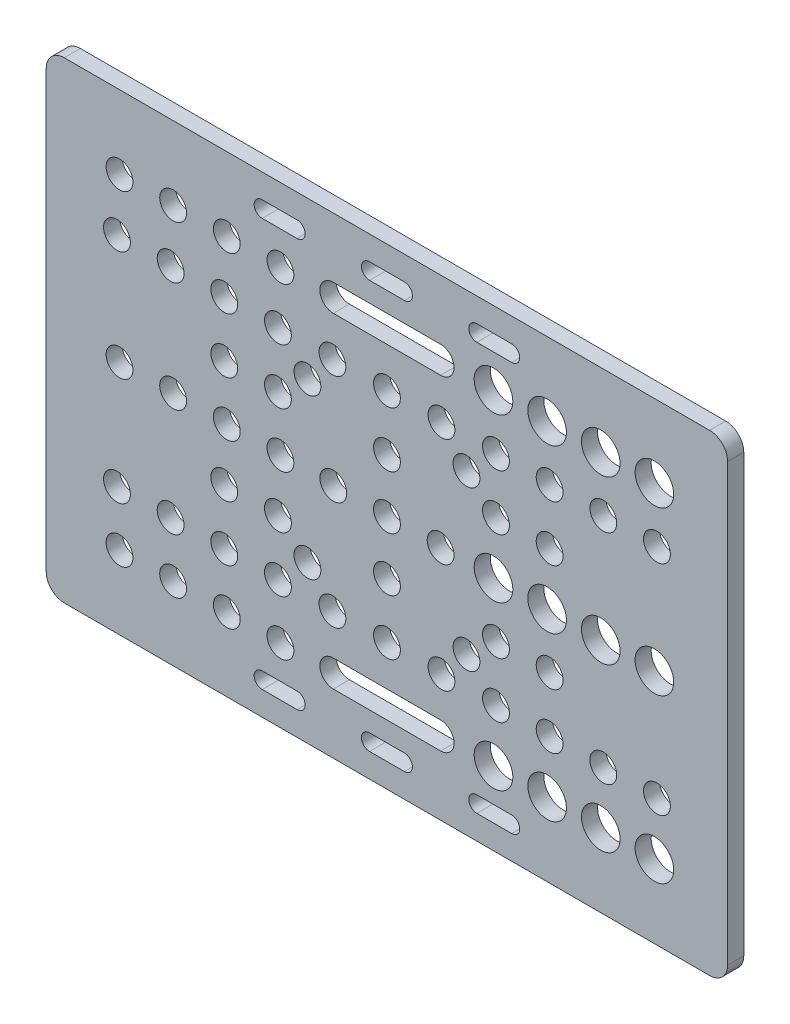
SolidWorks part; units mm, degrees
material "6063-T6"
ref_plane "Front" through (0, 0, 0) normal (0, 0, 1) x (1, 0, 0)
ref_plane "Top" through (0, 0, 0) normal (0, 1, 0) x (1, 0, 0)
ref_plane "Right" through (0, 0, 0) normal (1, 0, 0) x (0, 0, -1)
sketch "Sketch1" plane through (0, 0, 0) normal (0, 0, 1) x (1, 0, 0)
  line L0 (-60.14, 44) -> (-63.5, 40.64) construction
  line L1 (-60.14, -44) -> (60.14, -44)
  line L2 (-63.5, -40.64) -> (-63.5, 40.64)
  line L3 (-60.14, 44) -> (60.14, 44)
  line L4 (63.5, -40.64) -> (63.5, 40.64)
  line L5 (-62.924, -42.5213) -> (62.924, 42.5213) construction
  line L6 (-62.924, 42.5213) -> (62.924, -42.5213) construction
  line L7 (60.14, 44) -> (63.5, 40.64) construction
  line L8 (63.5, -40.64) -> (60.14, -44) construction
  line L9 (-63.5, -40.64) -> (-60.14, -44) construction
  line L10 (-63.5, 0) -> (63.5, 0) construction
  line L11 (0, 44) -> (0, -44) construction
  line L12 (-63.5, -30.32) -> (63.5, -30.32) construction
  line L13 (-10, -30.32) -> (10, -30.32) construction
  line L14 (-10, -27.82) -> (10, -27.82)
  line L15 (-10, -32.82) -> (10, -32.82)
  line L16 (-10, 30.32) -> (10, 30.32) construction
  line L17 (-10, 27.82) -> (10, 27.82)
  line L18 (-10, 32.82) -> (10, 32.82)
  line L19 (-63.5, -38.02) -> (63.5, -38.02) construction
  line L20 (-3.25, -38.02) -> (3.25, -38.02) construction
  line L21 (-3.25, -36.52) -> (3.25, -36.52)
  line L22 (-3.25, -39.52) -> (3.25, -39.52)
  line L23 (-23.25, -38.02) -> (-16.75, -38.02) construction
  line L24 (-23.25, -36.52) -> (-16.75, -36.52)
  line L25 (-23.25, -39.52) -> (-16.75, -39.52)
  line L26 (23.25, -38.02) -> (16.75, -38.02) construction
  line L27 (23.25, -36.52) -> (16.75, -36.52)
  line L28 (23.25, -39.52) -> (16.75, -39.52)
  line L29 (-23.25, 38.02) -> (-16.75, 38.02) construction
  line L30 (-23.25, 36.52) -> (-16.75, 36.52)
  line L31 (-23.25, 39.52) -> (-16.75, 39.52)
  line L32 (-3.25, 38.02) -> (3.25, 38.02) construction
  line L33 (-3.25, 36.52) -> (3.25, 36.52)
  line L34 (-3.25, 39.52) -> (3.25, 39.52)
  line L35 (23.25, 38.02) -> (16.75, 38.02) construction
  line L36 (23.25, 36.52) -> (16.75, 36.52)
  line L37 (23.25, 39.52) -> (16.75, 39.52)
  line L38 (-63.5, -20.32) -> (63.5, -20.32) construction
  line L39 (-63.5, -10) -> (63.5, -10) construction
  line L40 (-63.5, -14.82) -> (63.5, -14.82) construction
  arc A0 (-60.14, 44) -> (-63.5, 40.64) centre (-60.14, 40.64) ccw
  arc A1 (63.5, 40.64) -> (60.14, 44) centre (60.14, 40.64) ccw
  arc A2 (60.14, -44) -> (63.5, -40.64) centre (60.14, -40.64) ccw
  arc A3 (-63.5, -40.64) -> (-60.14, -44) centre (-60.14, -40.64) ccw
  circle A4 centre (0, 0) radius 2.5
  circle A5 centre (-49.845, 0) radius 2.5
  circle A6 centre (49.845, 0) radius 3.6
  circle A7 centre (-19.855, -30.32) radius 2.5
  circle A8 centre (19.855, -30.32) radius 3.6
  circle A9 centre (-29.85, -30.32) radius 2.5
  circle A10 centre (-39.85, -30.32) radius 2.5
  circle A11 centre (-49.845, -30.32) radius 2.5
  circle A12 centre (49.845, -30.32) radius 3.6
  circle A13 centre (39.85, -30.32) radius 3.6
  circle A14 centre (29.85, -30.32) radius 3.6
  circle A15 centre (49.845, 30.32) radius 3.6
  circle A16 centre (39.85, 30.32) radius 3.6
  circle A17 centre (29.85, 30.32) radius 3.6
  circle A18 centre (19.855, 30.32) radius 3.6
  circle A19 centre (-19.855, 30.32) radius 2.5
  circle A20 centre (-29.85, 30.32) radius 2.5
  circle A21 centre (-39.85, 30.32) radius 2.5
  circle A22 centre (-49.845, 30.32) radius 2.5
  arc A23 (-10, -27.82) -> (-10, -32.82) centre (-10, -30.32) ccw
  arc A24 (10, -32.82) -> (10, -27.82) centre (10, -30.32) ccw
  arc A25 (-10, 27.82) -> (-10, 32.82) centre (-10, 30.32) cw
  arc A26 (10, 32.82) -> (10, 27.82) centre (10, 30.32) cw
  arc A27 (-3.25, -36.52) -> (-3.25, -39.52) centre (-3.25, -38.02) ccw
  arc A28 (3.25, -39.52) -> (3.25, -36.52) centre (3.25, -38.02) ccw
  arc A29 (-23.25, -36.52) -> (-23.25, -39.52) centre (-23.25, -38.02) ccw
  arc A30 (-16.75, -39.52) -> (-16.75, -36.52) centre (-16.75, -38.02) ccw
  arc A31 (23.25, -36.52) -> (23.25, -39.52) centre (23.25, -38.02) cw
  arc A32 (16.75, -39.52) -> (16.75, -36.52) centre (16.75, -38.02) cw
  arc A33 (-23.25, 36.52) -> (-23.25, 39.52) centre (-23.25, 38.02) cw
  arc A34 (-16.75, 39.52) -> (-16.75, 36.52) centre (-16.75, 38.02) cw
  arc A35 (-3.25, 36.52) -> (-3.25, 39.52) centre (-3.25, 38.02) cw
  arc A36 (3.25, 39.52) -> (3.25, 36.52) centre (3.25, 38.02) cw
  arc A37 (23.25, 36.52) -> (23.25, 39.52) centre (23.25, 38.02) ccw
  arc A38 (16.75, 39.52) -> (16.75, 36.52) centre (16.75, 38.02) ccw
  circle A39 centre (-50.32, -20.32) radius 2.5
  circle A40 centre (-40.32, -20.32) radius 2.5
  circle A41 centre (-30.32, -20.32) radius 2.5
  circle A42 centre (-20.32, -20.32) radius 2.5
  circle A43 centre (50.32, -20.32) radius 2.5
  circle A44 centre (40.32, -20.32) radius 2.5
  circle A45 centre (30.32, -20.32) radius 2.5
  circle A46 centre (20.32, -20.32) radius 2.5
  circle A47 centre (50.32, 20.32) radius 2.5
  circle A48 centre (40.32, 20.32) radius 2.5
  circle A49 centre (30.32, 20.32) radius 2.5
  circle A50 centre (20.32, 20.32) radius 2.5
  circle A51 centre (-20.32, 20.32) radius 2.5
  circle A52 centre (-30.32, 20.32) radius 2.5
  circle A53 centre (-40.32, 20.32) radius 2.5
  circle A54 centre (-50.32, 20.32) radius 2.5
  circle A55 centre (-39.85, 0) radius 2.5
  circle A56 centre (-29.85, 0) radius 2.5
  circle A57 centre (-19.855, 0) radius 2.5
  circle A58 centre (39.85, 0) radius 3.6
  circle A59 centre (29.85, 0) radius 3.6
  circle A60 centre (19.855, 0) radius 3.6
  circle A61 centre (0, -20.32) radius 2.5
  circle A62 centre (0, 20.32) radius 2.5
  circle A63 centre (-10.16, -20.32) radius 2.5
  circle A64 centre (10.16, -20.32) radius 2.5
  circle A65 centre (10.16, 20.32) radius 2.5
  circle A66 centre (-10.16, 20.32) radius 2.5
  circle A67 centre (-10, 0) radius 2.5
  circle A68 centre (10, 0) radius 2.5
  circle A69 centre (0, -10) radius 2.5
  circle A70 centre (0, 10) radius 2.5
  circle A71 centre (-30.32, -10) radius 2.5
  circle A72 centre (-20.32, -10) radius 2.5
  circle A73 centre (30.32, -10) radius 2.5
  circle A74 centre (20.32, -10) radius 2.5
  circle A75 centre (30.32, 10) radius 2.5
  circle A76 centre (20.32, 10) radius 2.5
  circle A77 centre (-30.32, 10) radius 2.5
  circle A78 centre (-20.32, 10) radius 2.5
  circle A79 centre (-14.82, -14.82) radius 2.5
  circle A80 centre (14.82, -14.82) radius 2.5
  circle A81 centre (14.82, 14.82) radius 2.5
  circle A82 centre (-14.82, 14.82) radius 2.5
  point P0 (0, 0)
  point P64 (0, -30.32)
  point P71 (0, 30.32)
  point P80 (0, -38.02)
  point P87 (-20, -38.02)
  point P94 (20, -38.02)
  point P101 (-20, 38.02)
  point P108 (0, 38.02)
  point P115 (20, 38.02)
  point P166 (0, -20.32)
  dimension "D1" = 3.36
  dimension "D4" = 5
  dimension "D5" = 7.2
  dimension "D7" = 13.68
  dimension "D11" = 25
  dimension "D14" = 9.5
  dimension "D16" = 10.5
  dimension "D20" = 5
  dimension "D21" = 5
  dimension "D22" = 5
  dimension "D23" = 5
  dimension "D24" = 5
  dimension "D25" = 5.16
  dimension "D26" = 29.18
  dimension "D2" = 88
  dimension "D3" = 127
  dimension "D6" = 39.71
  dimension "D8" = 59.7
  dimension "D9" = 79.7
  dimension "D10" = 99.69
  dimension "D12" = 5
  dimension "D13" = 3
  dimension "D15" = 5.98
  dimension "D17" = 3
  dimension "D18" = 10
  dimension "D19" = 13.18
  dimension "D27" = 14.82
extrude "Boss-Extrude1" add sketch "Sketch1" along normal blind 3
